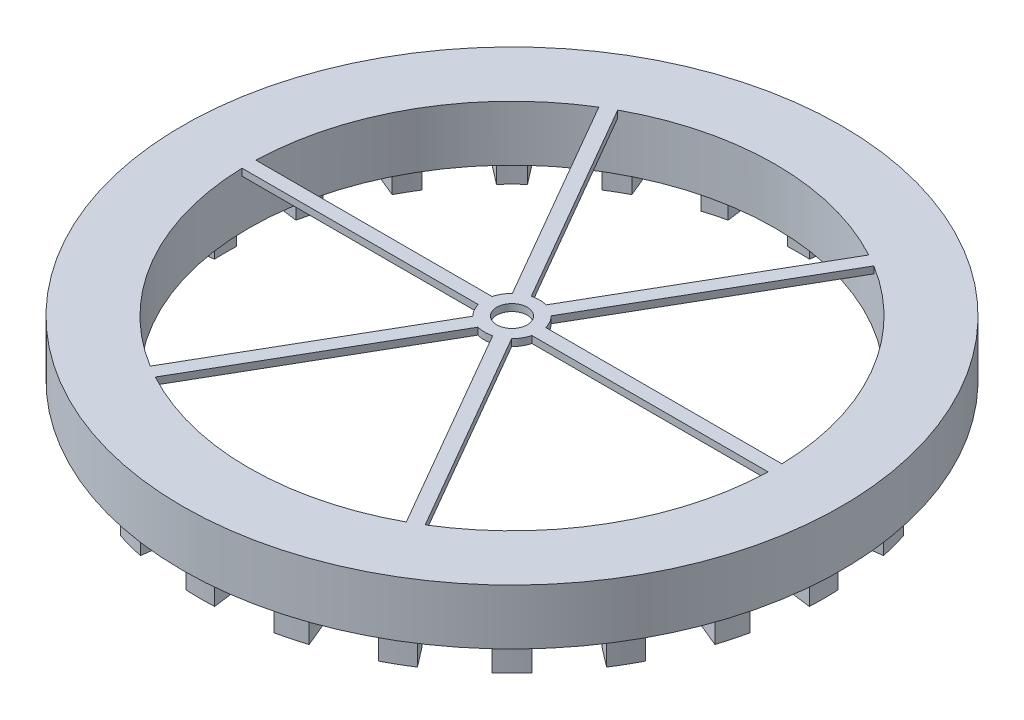
SolidWorks part; units mm, degrees
ref_plane "Front Plane" through (0, 0, 0) normal (0, 0, 1) x (1, 0, 0)
ref_plane "Top Plane" through (0, 0, 0) normal (0, 1, 0) x (1, 0, 0)
ref_plane "Right Plane" through (0, 0, 0) normal (1, 0, 0) x (0, 0, -1)
sketch "Sketch1" plane through (0, 0, 0) normal (0, 1, 0) x (1, 0, 0)
  line L0 (0, 0) -> (0, 130.6457) construction
  line L1 (0, 0) -> (-74.3722, 128.8163) construction
  circle A0 centre (0, 0) radius 119
  circle A1 centre (0, 0) radius 5.5
  dimension "D1" = 238
  dimension "D2" = 11
  dimension "D3" = 30
extrude "Boss-Extrude1" add sketch "Sketch1" along normal mid plane 20
sketch "Sketch2" plane through (0, -10, 0) normal (0, 1, 0) x (1, 0, 0)
  line L0 (5.15, -112.525) -> (3.9585, -103.475)
  line L1 (-3.9585, -103.475) -> (-5.15, -112.525)
  line L2 (0, 0) -> (0, -119) construction
  line L3 (-4.5543, -108) -> (4.5543, -108) construction
  line L4 (-24.1491, -110.0237) -> (-22.9576, -100.9737)
  line L5 (-30.605, -98.9246) -> (-34.0981, -107.3579)
  line L6 (-51.8025, -100.0245) -> (-48.3093, -91.5913)
  line L7 (-55.1657, -87.6327) -> (-60.7225, -94.8745)
  line L8 (-75.9256, -83.2088) -> (-70.3688, -75.967)
  line L9 (-75.967, -70.3688) -> (-83.2088, -75.9256)
  line L10 (-94.8745, -60.7225) -> (-87.6327, -55.1657)
  line L11 (-91.5913, -48.3093) -> (-100.0245, -51.8025)
  line L12 (-107.3579, -34.0981) -> (-98.9246, -30.605)
  line L13 (-100.9737, -22.9576) -> (-110.0237, -24.1491)
  line L14 (-112.525, -5.15) -> (-103.475, -3.9585)
  line L15 (-103.475, 3.9585) -> (-112.525, 5.15)
  line L16 (-110.0237, 24.1491) -> (-100.9737, 22.9576)
  line L17 (-98.9246, 30.605) -> (-107.3579, 34.0981)
  line L18 (-100.0245, 51.8025) -> (-91.5913, 48.3093)
  line L19 (-87.6327, 55.1657) -> (-94.8745, 60.7225)
  line L20 (-83.2088, 75.9256) -> (-75.967, 70.3688)
  line L21 (-70.3688, 75.967) -> (-75.9256, 83.2088)
  line L22 (-60.7225, 94.8745) -> (-55.1657, 87.6327)
  line L23 (-48.3093, 91.5913) -> (-51.8025, 100.0245)
  line L24 (-34.0981, 107.3579) -> (-30.605, 98.9246)
  line L25 (-22.9576, 100.9737) -> (-24.1491, 110.0237)
  line L26 (-5.15, 112.525) -> (-3.9585, 103.475)
  line L27 (3.9585, 103.475) -> (5.15, 112.525)
  line L28 (24.1491, 110.0237) -> (22.9576, 100.9737)
  line L29 (30.605, 98.9246) -> (34.0981, 107.3579)
  line L30 (51.8025, 100.0245) -> (48.3093, 91.5913)
  line L31 (55.1657, 87.6327) -> (60.7225, 94.8745)
  line L32 (75.9256, 83.2088) -> (70.3688, 75.967)
  line L33 (75.967, 70.3688) -> (83.2088, 75.9256)
  line L34 (94.8745, 60.7225) -> (87.6327, 55.1657)
  line L35 (91.5913, 48.3093) -> (100.0245, 51.8025)
  line L36 (107.3579, 34.0981) -> (98.9246, 30.605)
  line L37 (100.9737, 22.9576) -> (110.0237, 24.1491)
  line L38 (112.525, 5.15) -> (103.475, 3.9585)
  line L39 (103.475, -3.9585) -> (112.525, -5.15)
  line L40 (110.0237, -24.1491) -> (100.9737, -22.9576)
  line L41 (98.9246, -30.605) -> (107.3579, -34.0981)
  line L42 (100.0245, -51.8025) -> (91.5913, -48.3093)
  line L43 (87.6327, -55.1657) -> (94.8745, -60.7225)
  line L44 (83.2088, -75.9256) -> (75.967, -70.3688)
  line L45 (70.3688, -75.967) -> (75.9256, -83.2088)
  line L46 (60.7225, -94.8745) -> (55.1657, -87.6327)
  line L47 (48.3093, -91.5913) -> (51.8025, -100.0245)
  line L48 (34.0981, -107.3579) -> (30.605, -98.9246)
  line L49 (22.9576, -100.9737) -> (24.1491, -110.0237)
  arc A0 (-3.9585, -103.475) -> (3.9585, -103.475) centre (0, -5.4602) ccw
  arc A1 (-5.15, -112.525) -> (5.15, -112.525) centre (0, -5.4602) ccw
  circle A2 centre (0, 0) radius 119 construction
  arc A3 (-30.605, -98.9246) -> (-22.9576, -100.9737) centre (-1.4132, -5.2742) ccw
  arc A4 (-34.0981, -107.3579) -> (-24.1491, -110.0237) centre (-1.4132, -5.2742) ccw
  arc A5 (-55.1657, -87.6327) -> (-48.3093, -91.5913) centre (-2.7301, -4.7287) ccw
  arc A6 (-60.7225, -94.8745) -> (-51.8025, -100.0245) centre (-2.7301, -4.7287) ccw
  arc A7 (-75.967, -70.3688) -> (-70.3688, -75.967) centre (-3.861, -3.861) ccw
  arc A8 (-83.2088, -75.9256) -> (-75.9256, -83.2088) centre (-3.861, -3.861) ccw
  arc A9 (-91.5913, -48.3093) -> (-87.6327, -55.1657) centre (-4.7287, -2.7301) ccw
  arc A10 (-100.0245, -51.8025) -> (-94.8745, -60.7225) centre (-4.7287, -2.7301) ccw
  arc A11 (-100.9737, -22.9576) -> (-98.9246, -30.605) centre (-5.2742, -1.4132) ccw
  arc A12 (-110.0237, -24.1491) -> (-107.3579, -34.0981) centre (-5.2742, -1.4132) ccw
  arc A13 (-103.475, 3.9585) -> (-103.475, -3.9585) centre (-5.4602, 0) ccw
  arc A14 (-112.525, 5.15) -> (-112.525, -5.15) centre (-5.4602, 0) ccw
  arc A15 (-98.9246, 30.605) -> (-100.9737, 22.9576) centre (-5.2742, 1.4132) ccw
  arc A16 (-107.3579, 34.0981) -> (-110.0237, 24.1491) centre (-5.2742, 1.4132) ccw
  arc A17 (-87.6327, 55.1657) -> (-91.5913, 48.3093) centre (-4.7287, 2.7301) ccw
  arc A18 (-94.8745, 60.7225) -> (-100.0245, 51.8025) centre (-4.7287, 2.7301) ccw
  arc A19 (-70.3688, 75.967) -> (-75.967, 70.3688) centre (-3.861, 3.861) ccw
  arc A20 (-75.9256, 83.2088) -> (-83.2088, 75.9256) centre (-3.861, 3.861) ccw
  arc A21 (-48.3093, 91.5913) -> (-55.1657, 87.6327) centre (-2.7301, 4.7287) ccw
  arc A22 (-51.8025, 100.0245) -> (-60.7225, 94.8745) centre (-2.7301, 4.7287) ccw
  arc A23 (-22.9576, 100.9737) -> (-30.605, 98.9246) centre (-1.4132, 5.2742) ccw
  arc A24 (-24.1491, 110.0237) -> (-34.0981, 107.3579) centre (-1.4132, 5.2742) ccw
  arc A25 (3.9585, 103.475) -> (-3.9585, 103.475) centre (0, 5.4602) ccw
  arc A26 (5.15, 112.525) -> (-5.15, 112.525) centre (0, 5.4602) ccw
  arc A27 (30.605, 98.9246) -> (22.9576, 100.9737) centre (1.4132, 5.2742) ccw
  arc A28 (34.0981, 107.3579) -> (24.1491, 110.0237) centre (1.4132, 5.2742) ccw
  arc A29 (55.1657, 87.6327) -> (48.3093, 91.5913) centre (2.7301, 4.7287) ccw
  arc A30 (60.7225, 94.8745) -> (51.8025, 100.0245) centre (2.7301, 4.7287) ccw
  arc A31 (75.967, 70.3688) -> (70.3688, 75.967) centre (3.861, 3.861) ccw
  arc A32 (83.2088, 75.9256) -> (75.9256, 83.2088) centre (3.861, 3.861) ccw
  arc A33 (91.5913, 48.3093) -> (87.6327, 55.1657) centre (4.7287, 2.7301) ccw
  arc A34 (100.0245, 51.8025) -> (94.8745, 60.7225) centre (4.7287, 2.7301) ccw
  arc A35 (100.9737, 22.9576) -> (98.9246, 30.605) centre (5.2742, 1.4132) ccw
  arc A36 (110.0237, 24.1491) -> (107.3579, 34.0981) centre (5.2742, 1.4132) ccw
  arc A37 (103.475, -3.9585) -> (103.475, 3.9585) centre (5.4602, 0) ccw
  arc A38 (112.525, -5.15) -> (112.525, 5.15) centre (5.4602, 0) ccw
  arc A39 (98.9246, -30.605) -> (100.9737, -22.9576) centre (5.2742, -1.4132) ccw
  arc A40 (107.3579, -34.0981) -> (110.0237, -24.1491) centre (5.2742, -1.4132) ccw
  arc A41 (87.6327, -55.1657) -> (91.5913, -48.3093) centre (4.7287, -2.7301) ccw
  arc A42 (94.8745, -60.7225) -> (100.0245, -51.8025) centre (4.7287, -2.7301) ccw
  arc A43 (70.3688, -75.967) -> (75.967, -70.3688) centre (3.861, -3.861) ccw
  arc A44 (75.9256, -83.2088) -> (83.2088, -75.9256) centre (3.861, -3.861) ccw
  arc A45 (48.3093, -91.5913) -> (55.1657, -87.6327) centre (2.7301, -4.7287) ccw
  arc A46 (51.8025, -100.0245) -> (60.7225, -94.8745) centre (2.7301, -4.7287) ccw
  arc A47 (22.9576, -100.9737) -> (30.605, -98.9246) centre (1.4132, -5.2742) ccw
  arc A48 (24.1491, -110.0237) -> (34.0981, -107.3579) centre (1.4132, -5.2742) ccw
  point P154 (0, 0)
  dimension "D1" = 108
  dimension "D2" = 10.3
  dimension "D3" = 9.05
  dimension "D4" = 15
  dimension "D5" = 24
extrude "Boss-Extrude2" add sketch "Sketch2" against normal blind 12
sketch "Sketch5" plane through (0, 10, 0) normal (0, -1, 0) x (1, 0, 0)
  circle A0 centre (0, 0) radius 20
  circle A1 centre (0, 0) radius 5.5
  dimension "D1" = 40
  dimension "D2" = 11
extrude "Boss-Extrude3" add sketch "Sketch5" along normal blind 10
sketch "Sketch6" plane through (0, -10, 0) normal (0, -1, 0) x (1, 0, 0)
  line L0 (9.6825, 2.5) -> (94.9671, 2.5)
  line L1 (5.5, 0) -> (95, 0) construction
  line L2 (9.6825, -2.5) -> (94.9671, -2.5)
  line L3 (2.6762, -9.6353) -> (45.3185, -83.4939)
  line L4 (7.0063, -7.1353) -> (49.6486, -80.9939)
  line L5 (-7.0063, -7.1353) -> (-49.6486, -80.9939)
  line L6 (-2.6762, -9.6353) -> (-45.3185, -83.4939)
  line L7 (-9.6825, 2.5) -> (-94.9671, 2.5)
  line L8 (-9.6825, -2.5) -> (-94.9671, -2.5)
  line L9 (-2.6762, 9.6353) -> (-45.3185, 83.4939)
  line L10 (-7.0063, 7.1353) -> (-49.6486, 80.9939)
  line L11 (7.0063, 7.1353) -> (49.6486, 80.9939)
  line L12 (2.6762, 9.6353) -> (45.3185, 83.4939)
  arc A0 (-49.6486, 80.9939) -> (-94.9671, 2.5) centre (0, 0) ccw
  circle A1 centre (0, 0) radius 5.5
  arc A3 (9.6825, 2.5) -> (7.0063, 7.1353) centre (0, 0) ccw
  arc A4 (2.6762, 9.6353) -> (-2.6762, 9.6353) centre (0, 0) ccw
  arc A5 (-7.0063, 7.1353) -> (-9.6825, 2.5) centre (0, 0) ccw
  arc A6 (-9.6825, -2.5) -> (-7.0063, -7.1353) centre (0, 0) ccw
  arc A7 (-2.6762, -9.6353) -> (2.6762, -9.6353) centre (0, 0) ccw
  arc A8 (7.0063, -7.1353) -> (9.6825, -2.5) centre (0, 0) ccw
  arc A9 (45.3185, 83.4939) -> (-45.3185, 83.4939) centre (0, 0) ccw
  arc A10 (94.9671, 2.5) -> (49.6486, 80.9939) centre (0, 0) ccw
  arc A11 (-94.9671, -2.5) -> (-49.6486, -80.9939) centre (0, 0) ccw
  arc A12 (-45.3185, -83.4939) -> (45.3185, -83.4939) centre (0, 0) ccw
  arc A13 (49.6486, -80.9939) -> (94.9671, -2.5) centre (0, 0) ccw
  point P34 (0, 0)
  dimension "D1" = 190
  dimension "D2" = 2.5
  dimension "D3" = 20
  dimension "D4" = 6
extrude "Cut-Extrude5" cut sketch "Sketch6" against normal blind 64
sketch "Sketch7" plane through (0, -10, 0) normal (0, -1, 0) x (-1, 0, 0)
  circle A0 centre (0, 0) radius 95
  arc A1 (-49.6486, 80.9939) -> (-94.9671, 2.5) centre (0, 0) ccw construction
extrude "Cut-Extrude6" cut sketch "Sketch7" against normal blind 17.5
